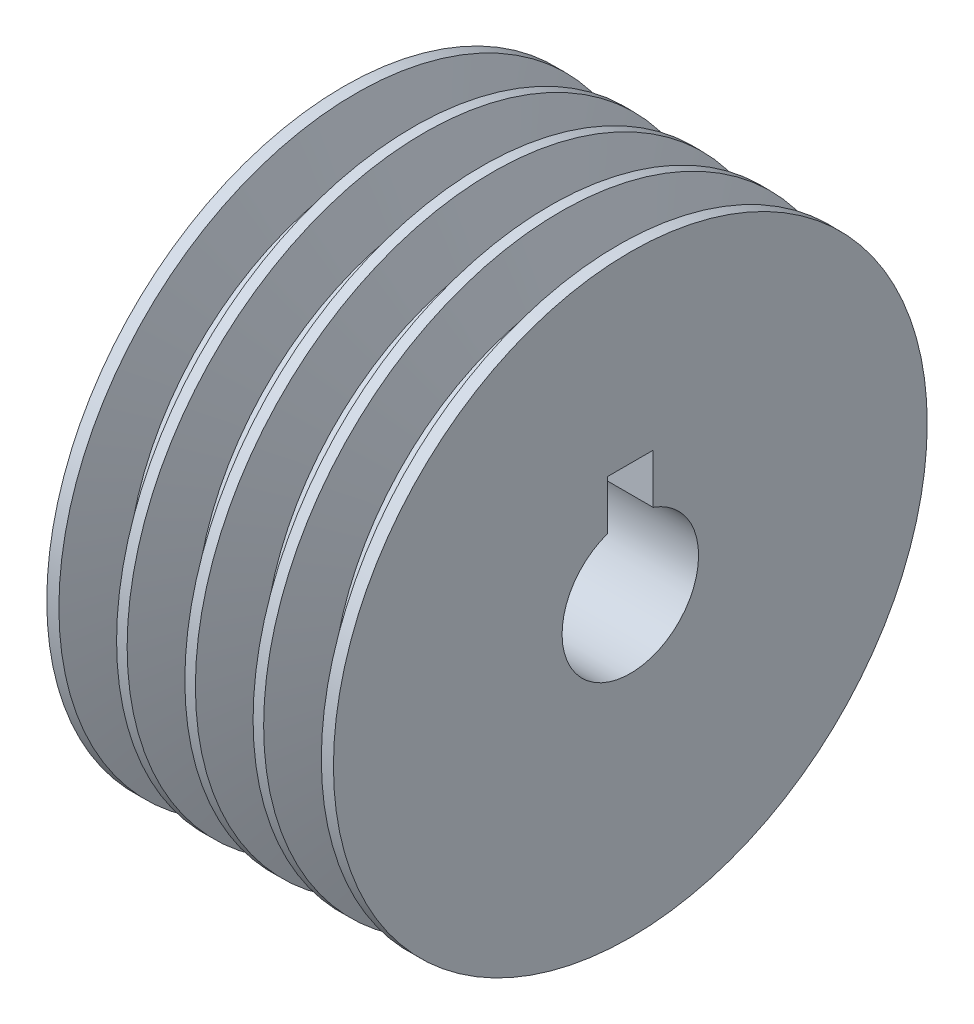
SolidWorks part; units mm, degrees
ref_plane "前视基准面" through (0, 0, 0) normal (0, 0, 1) x (1, 0, 0)
ref_plane "上视基准面" through (0, 0, 0) normal (0, 1, 0) x (1, 0, 0)
ref_plane "右视基准面" through (0, 0, 0) normal (1, 0, 0) x (0, 0, -1)
sketch "草图1" plane through (0, 0, 0) normal (1, 0, 0) x (0, 0, -1)
  line L0 (-5, 14.1421) -> (-5, 25)
  line L1 (0, 0) -> (0, -50000) construction
  line L2 (0, 0) -> (50000, 0) construction
  line L3 (-5, 25) -> (5, 25)
  line L7 (5, 14.1421) -> (5, 25)
  circle A0 centre (0, 0) radius 65.25
  arc A1 (-5, 14.1421) -> (5, 14.1421) centre (0, 0) ccw
  point P3 (0, 0)
  dimension "D1" = 130.5
  dimension "D2" = 30
  dimension "D3" = 10
  dimension "D4" = 25
extrude "凸台-拉伸1" add sketch "草图1" along normal mid plane 63
sketch "草图2" plane through (0, 0, 0) normal (0, 0, 1) x (1, 0, 0)
  line L0 (0, 0) -> (50000, 0) construction
  line L1 (-31.5, 65.25) -> (-31.5, -65.25) construction
  line L2 (-28.8408, 65.25) -> (-16.1592, 65.25)
  line L3 (-22.5, 65.25) -> (-22.5, 53.8) construction
  line L4 (31.5, 65.25) -> (-31.5, 65.25) construction
  line L14 (-28.8408, 65.25) -> (-25.3401, 53.8)
  line L15 (-25.3401, 53.8) -> (-19.6599, 53.8)
  line L16 (-19.6599, 53.8) -> (-16.1592, 65.25)
  line L22 (-28, 62.5) -> (-17, 62.5) construction
  point P8 (0, 0)
  dimension "D1" = 9
  dimension "D2" = 2.75
  dimension "D3" = 11
  dimension "D4" = 8.7
  dimension "D5" = 34
revolve "切除-旋转1" cut sketch "草图2" angle 360 about L0
pattern_linear "阵列(线性)1" count 4 spacing 15 along (1, 0, 0) of "切除-旋转1"
